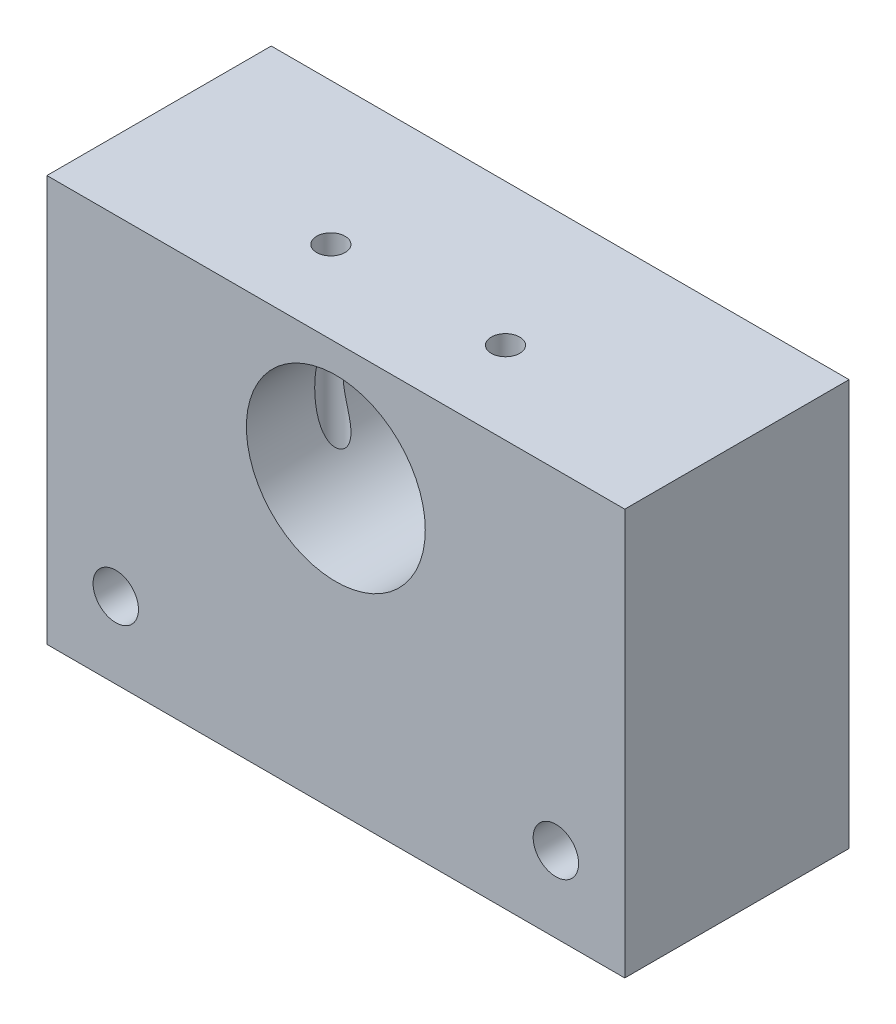
SolidWorks part; units mm, degrees
ref_plane "Спереди" through (0, 0, 0) normal (0, 0, 1) x (1, 0, 0)
ref_plane "Сверху" through (0, 0, 0) normal (0, 1, 0) x (1, 0, 0)
ref_plane "Справа" through (0, 0, 0) normal (1, 0, 0) x (0, 0, -1)
sketch "Эскиз1" plane through (0, 0, 0) normal (0, 0, 1) x (1, 0, 0)
  line L1 (0, 0) -> (40.7, 0)
  line L2 (0, 0) -> (0, 28.6)
  line L3 (0, 28.6) -> (40.7, 28.6)
  line L4 (40.7, 0) -> (40.7, 28.6)
  dimension "D1" = 40.7
  dimension "D2" = 28.6
extrude "Бобышка-Вытянуть1" add sketch "Эскиз1" along normal blind 15.8
sketch "Эскиз2" plane through (0, 0, 15.8) normal (0, 0, 1) x (1, 0, 0)
  line L0 (40.7, 0) -> (40.7, 28.6) construction
  line L1 (0, 28.6) -> (0, 0) construction
  line L2 (0, 0) -> (40.7, 0) construction
  line L3 (20.35, 0) -> (20.35, 28.9735) construction
  line L4 (0, 0) -> (40.7, 0) construction
  line L5 (40.7, 28.6) -> (0, 28.6) construction
  circle A0 centre (35.85, 5.35) radius 1.6
  circle A1 centre (4.85, 5.35) radius 1.6
  circle A2 centre (20.35, 20.3) radius 6.3
  dimension "D1" = 3.2
  dimension "D2" = 31
  dimension "D3" = 4.85
  dimension "D5" = 5.35
  dimension "D6" = 12.6
  dimension "D4" = 4.85
  dimension "D7" = 8.3
extrude "Вырез-Вытянуть1" cut sketch "Эскиз2" against normal through all
sketch "Эскиз3" plane through (0, 0, 0) normal (0, -1, 0) x (1, 0, 0)
  line L0 (0, 15.8) -> (0, 0) construction
  line L1 (40.7, 15.8) -> (40.7, 0) construction
  line L2 (0, 0) -> (40.7, 0) construction
  circle A0 centre (14.2, 10) radius 1
  circle A1 centre (26.5, 10) radius 1
  dimension "D1" = 2
  dimension "D2" = 14.2
  dimension "D3" = 14.2
  dimension "D4" = 10
  dimension "D5" = 10
extrude "Вырез-Вытянуть2" cut sketch "Эскиз3" against normal through all
